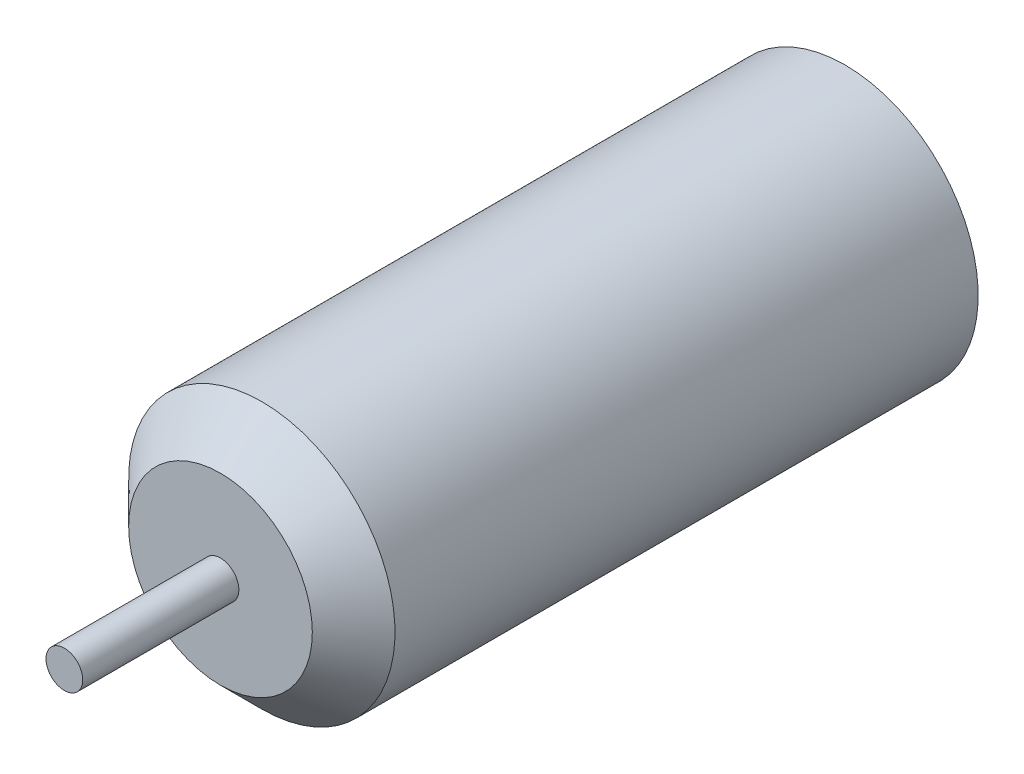
SolidWorks part; units mm, degrees
ref_plane "Front Plane" through (0, 0, 0) normal (0, 0, 1) x (1, 0, 0)
ref_plane "Top Plane" through (0, 0, 0) normal (0, 1, 0) x (1, 0, 0)
ref_plane "Right Plane" through (0, 0, 0) normal (1, 0, 0) x (0, 0, -1)
sketch "Sketch3" plane through (0, 0, 0) normal (1, 0, 0) x (0, 0, -1)
  line L0 (0, 0) -> (0, 2)
  line L1 (0, 2) -> (17, 2)
  line L2 (17, 2) -> (17, 10)
  line L3 (17, 10) -> (21.5, 14.5)
  line L4 (21.5, 14.5) -> (85, 14.5)
  line L6 (85, 14.5) -> (85, 0)
  line L7 (85, 0) -> (0, 0)
  dimension "D1" = 2
  dimension "D2" = 68
  dimension "D3" = 14.5
  dimension "D4" = 63.5
  dimension "D5" = 85
  dimension "D6" = 135
revolve "Revolve1" add sketch "Sketch3" angle 360 about L7
